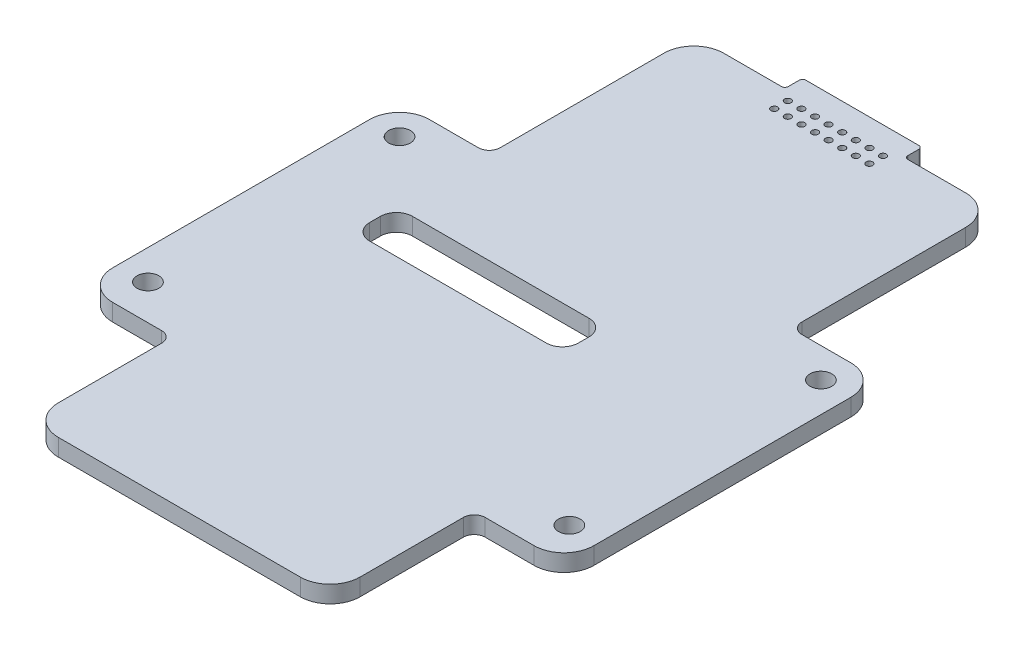
SolidWorks part; units mm, degrees
ref_plane "Front Plane" through (0, 0, 0) normal (0, 0, 1) x (1, 0, 0)
ref_plane "Top Plane" through (0, 0, 0) normal (0, 1, 0) x (1, 0, 0)
ref_plane "Right Plane" through (0, 0, 0) normal (1, 0, 0) x (0, 0, -1)
sketch "Sketch6" plane through (0, 3.4925, 0) normal (0, 1, 0) x (1, 0, 0)
  line L0 (19.685, 17.018) -> (15.113, 17.018) construction
  line L1 (11.303, 39.3065) -> (-11.303, 39.3065)
  line L2 (-14.097, 36.5125) -> (-14.097, 17.653)
  line L3 (11.303, 39.6875) -> (-11.303, 39.6875) construction
  line L4 (-14.478, 36.5125) -> (-14.478, 17.653) construction
  line L5 (-15.113, 17.018) -> (-19.685, 17.018) construction
  line L9 (14.478, 17.653) -> (14.478, 36.5125) construction
  line L10 (11.303, 39.6875) -> (-11.303, 39.6875)
  line L11 (-14.478, 36.5125) -> (-14.478, 17.653)
  line L12 (-15.113, 17.018) -> (-19.685, 17.018)
  line L16 (19.685, 17.018) -> (15.113, 17.018)
  line L17 (14.478, 17.653) -> (14.478, 36.5125)
  line L18 (-15.113, 16.637) -> (-19.685, 16.637)
  line L22 (19.685, 16.637) -> (15.113, 16.637)
  line L23 (14.097, 17.653) -> (14.097, 36.5125)
  line L24 (22.86, -13.843) -> (22.86, 13.843) construction
  line L25 (11.303, 35.7505) -> (5.9055, 35.7505)
  line L26 (-5.588, 36.068) -> (-5.588, 37.084)
  line L27 (-5.2705, 37.4015) -> (5.2705, 37.4015)
  line L28 (5.588, 37.084) -> (5.588, 36.068)
  line L29 (-5.9055, 35.7505) -> (-11.303, 35.7505)
  line L33 (15.113, -17.018) -> (19.685, -17.018) construction
  line L34 (14.478, -27.305) -> (14.478, -17.653) construction
  line L35 (-11.303, -30.48) -> (11.303, -30.48) construction
  line L36 (-14.478, -17.653) -> (-14.478, -27.305) construction
  line L37 (-19.685, -17.018) -> (-15.113, -17.018) construction
  line L38 (-22.86, 13.843) -> (-22.86, -13.843) construction
  line L39 (22.86, -13.843) -> (22.86, 13.843)
  line L40 (15.113, -17.018) -> (19.685, -17.018)
  line L41 (14.478, -27.305) -> (14.478, -17.653)
  line L42 (-11.303, -30.48) -> (11.303, -30.48)
  line L43 (-22.86, 13.843) -> (-22.86, -13.843) construction
  line L44 (-19.685, -17.018) -> (19.685, -17.018) construction
  line L45 (22.86, -13.843) -> (22.86, 13.843) construction
  line L46 (-22.479, 13.843) -> (-22.479, -13.843) construction
  line L47 (22.479, -13.843) -> (22.479, 13.843) construction
  line L48 (-14.478, -17.653) -> (-14.478, -27.305)
  line L49 (-19.685, -17.018) -> (-15.113, -17.018)
  line L50 (-22.86, 13.843) -> (-22.86, -13.843)
  line L51 (22.479, -13.843) -> (22.479, 13.843)
  line L52 (19.685, 16.637) -> (15.113, 16.637)
  line L53 (-19.685, -16.637) -> (19.685, -16.637) construction
  line L54 (14.097, 17.653) -> (14.097, 36.5125)
  line L55 (11.303, 39.3065) -> (-11.303, 39.3065)
  line L56 (-14.097, 36.5125) -> (-14.097, 17.653)
  line L57 (-15.113, 16.637) -> (-19.685, 16.637)
  line L58 (-22.479, 13.843) -> (-22.479, -13.843)
  line L59 (-19.685, -16.637) -> (-15.113, -16.637)
  line L60 (-14.097, -17.653) -> (-14.097, -27.305)
  line L61 (-11.303, -30.099) -> (11.303, -30.099)
  line L62 (14.097, -27.305) -> (14.097, -17.653)
  line L63 (15.113, -16.637) -> (19.685, -16.637)
  line L64 (15.113, -12.954) -> (19.685, -12.954)
  line L65 (14.097, -23.622) -> (14.097, -13.97)
  line L66 (-11.303, -26.416) -> (11.303, -26.416)
  line L67 (-14.097, -13.97) -> (-14.097, -23.622)
  line L68 (-19.685, -12.954) -> (-15.113, -12.954)
  arc A0 (22.86, 13.843) -> (19.685, 17.018) centre (19.685, 13.843) ccw construction
  arc A1 (14.478, 36.5125) -> (11.303, 39.6875) centre (11.303, 36.5125) ccw construction
  arc A2 (-11.303, 39.6875) -> (-14.478, 36.5125) centre (-11.303, 36.5125) ccw construction
  arc A3 (-15.113, 17.018) -> (-14.478, 17.653) centre (-15.113, 17.653) ccw construction
  arc A4 (-19.685, 17.018) -> (-22.86, 13.843) centre (-19.685, 13.843) ccw construction
  arc A7 (14.478, 17.653) -> (15.113, 17.018) centre (15.113, 17.653) ccw construction
  arc A8 (14.478, 36.5125) -> (11.303, 39.6875) centre (11.303, 36.5125) ccw
  arc A9 (-11.303, 39.6875) -> (-14.478, 36.5125) centre (-11.303, 36.5125) ccw
  arc A10 (-15.113, 17.018) -> (-14.478, 17.653) centre (-15.113, 17.653) ccw
  arc A11 (-19.685, 17.018) -> (-22.86, 13.843) centre (-19.685, 13.843) ccw
  arc A14 (22.86, 13.843) -> (19.685, 17.018) centre (19.685, 13.843) ccw
  arc A15 (14.478, 17.653) -> (15.113, 17.018) centre (15.113, 17.653) ccw
  arc A16 (-11.303, 39.3065) -> (-14.097, 36.5125) centre (-11.303, 36.5125) ccw
  arc A17 (-15.113, 16.637) -> (-14.097, 17.653) centre (-15.113, 17.653) ccw
  arc A18 (-19.685, 16.637) -> (-22.479, 13.843) centre (-19.685, 13.843) ccw
  arc A21 (22.479, 13.843) -> (19.685, 16.637) centre (19.685, 13.843) ccw
  arc A22 (14.097, 17.653) -> (15.113, 16.637) centre (15.113, 17.653) ccw
  arc A23 (14.097, 36.5125) -> (11.303, 39.3065) centre (11.303, 36.5125) ccw
  arc A24 (19.685, -17.018) -> (22.86, -13.843) centre (19.685, -13.843) ccw construction
  arc A25 (15.113, -17.018) -> (14.478, -17.653) centre (15.113, -17.653) ccw construction
  arc A26 (-11.303, 35.7505) -> (-14.097, 32.9565) centre (-11.303, 32.9565) ccw
  arc A27 (14.097, 32.9565) -> (11.303, 35.7505) centre (11.303, 32.9565) ccw
  arc A28 (5.588, 36.068) -> (5.9055, 35.7505) centre (5.9055, 36.068) ccw
  arc A29 (5.2705, 37.4015) -> (5.588, 37.084) centre (5.2705, 37.084) cw
  arc A30 (-5.588, 37.084) -> (-5.2705, 37.4015) centre (-5.2705, 37.084) cw
  arc A31 (-5.588, 36.068) -> (-5.9055, 35.7505) centre (-5.9055, 36.068) cw
  arc A36 (11.303, -30.48) -> (14.478, -27.305) centre (11.303, -27.305) ccw construction
  arc A37 (-14.478, -27.305) -> (-11.303, -30.48) centre (-11.303, -27.305) ccw construction
  arc A38 (-14.478, -17.653) -> (-15.113, -17.018) centre (-15.113, -17.653) ccw construction
  arc A39 (-22.86, -13.843) -> (-19.685, -17.018) centre (-19.685, -13.843) ccw construction
  arc A40 (19.685, -17.018) -> (22.86, -13.843) centre (19.685, -13.843) ccw
  arc A41 (15.113, -17.018) -> (14.478, -17.653) centre (15.113, -17.653) ccw
  arc A42 (11.303, -30.48) -> (14.478, -27.305) centre (11.303, -27.305) ccw
  arc A43 (-14.478, -27.305) -> (-11.303, -30.48) centre (-11.303, -27.305) ccw
  arc A44 (-14.478, -17.653) -> (-15.113, -17.018) centre (-15.113, -17.653) ccw
  arc A45 (-22.86, -13.843) -> (-19.685, -17.018) centre (-19.685, -13.843) ccw
  arc A46 (22.479, 13.843) -> (19.685, 16.637) centre (19.685, 13.843) ccw
  arc A47 (14.097, 17.653) -> (15.113, 16.637) centre (15.113, 17.653) ccw
  arc A49 (14.097, 36.5125) -> (11.303, 39.3065) centre (11.303, 36.5125) ccw
  arc A50 (-11.303, 39.3065) -> (-14.097, 36.5125) centre (-11.303, 36.5125) ccw
  arc A51 (-22.86, -13.843) -> (-19.685, -17.018) centre (-19.685, -13.843) ccw construction
  arc A52 (19.685, -17.018) -> (22.86, -13.843) centre (19.685, -13.843) ccw construction
  arc A53 (-22.479, -13.843) -> (-19.685, -16.637) centre (-19.685, -13.843) ccw construction
  arc A54 (19.685, -16.637) -> (22.479, -13.843) centre (19.685, -13.843) ccw construction
  arc A55 (-15.113, 16.637) -> (-14.097, 17.653) centre (-15.113, 17.653) ccw
  arc A56 (-19.685, 16.637) -> (-22.479, 13.843) centre (-19.685, 13.843) ccw
  arc A57 (-22.479, -13.843) -> (-19.685, -16.637) centre (-19.685, -13.843) ccw
  arc A58 (-14.097, -17.653) -> (-15.113, -16.637) centre (-15.113, -17.653) ccw
  arc A59 (-14.097, -27.305) -> (-11.303, -30.099) centre (-11.303, -27.305) ccw
  arc A60 (11.303, -30.099) -> (14.097, -27.305) centre (11.303, -27.305) ccw
  arc A61 (15.113, -16.637) -> (14.097, -17.653) centre (15.113, -17.653) ccw
  arc A62 (19.685, -16.637) -> (22.479, -13.843) centre (19.685, -13.843) ccw
  arc A63 (19.685, -12.954) -> (22.479, -10.16) centre (19.685, -10.16) ccw
  arc A64 (15.113, -12.954) -> (14.097, -13.97) centre (15.113, -13.97) ccw
  arc A65 (11.303, -26.416) -> (14.097, -23.622) centre (11.303, -23.622) ccw
  arc A66 (-14.097, -23.622) -> (-11.303, -26.416) centre (-11.303, -23.622) ccw
  arc A67 (-14.097, -13.97) -> (-15.113, -12.954) centre (-15.113, -13.97) ccw
  arc A68 (-22.479, -10.16) -> (-19.685, -12.954) centre (-19.685, -10.16) ccw
  point P66 (0, 37.4015)
  point P77 (-5.588, 35.7505)
  line M1 (14.478, 17.653) -> (14.478, -13.843)
  circle M9 centre (19.685, -6.223) radius 1.27
  circle M10 centre (19.685, 13.843) radius 1.27
  circle M73 centre (-7.0168, -21.209) radius 1.27
  arc M74 (14.478, -13.843) -> (11.303, -17.018) centre (11.303, -13.843) cw
  line M75 (11.303, -17.018) -> (-9.4615, -17.018)
  line M76 (-9.4615, -17.018) -> (-9.4615, -25.4)
  line M77 (-9.4615, -25.4) -> (12.7, -25.4)
  arc M78 (12.7, -25.4) -> (15.875, -22.225) centre (12.7, -22.225) ccw
  dimension "D8" = 0.3175
  dimension "D3" = 2
  dimension "D5" = 3.556
  dimension "D6" = 1.651
  dimension "D7" = 11.176
  dimension "D9" = 4.064
  dimension "D1" = 0.381
  dimension "D2" = 0.381
  dimension "D4" = 2
extrude "Boss-Extrude1" add sketch "Sketch6" along normal blind 1.6 contours L58 A68 L68 A67 L67 L60 A66 L66 A65 L65 A64 A22 L23 A27 L25 A28 L28 A29 L27 A30 L26 A31 L29 A26 L56 A17 L18 A18 M78 M77 M76 M75 M74 M1 | M9 | A64 L64 A63 L51 A21 L22 A22 M1 M9 M10 | M10 | A65 L62 L65 M78 M74 M75 M76 M77 M73 | M73
sketch "Sketch2" plane through (0, 3.4925, 0) normal (0, 1, 0) x (1, 0, 0)
  line L0 (0, -0.88) -> (0, 0.88) construction
  line L1 (19.685, 13.843) -> (19.685, -9.66) construction
  circle A0 centre (19.685, 13.843) radius 1.016
  circle A1 centre (19.685, -9.66) radius 1.016
  circle A2 centre (-19.685, -9.66) radius 1.016
  circle A3 centre (-19.685, 13.843) radius 1.016
  arc A4 (22.479, 13.843) -> (19.685, 16.637) centre (19.685, 13.843) ccw construction
  point P12 (19.685, -10.16)
  dimension "D1" = 2.032
  dimension "D2" = 0.5
extrude "Cut-Extrude1" cut sketch "Sketch2" along normal through all contours A3 | A0 | A1 | A2
sketch "Sketch3" plane through (0, 3.4925, 0) normal (0, 1, 0) x (1, 0, 0)
  line L0 (-4.6482, 33.8162) -> (-4.2418, 33.4098) construction
  circle A0 centre (-4.445, 33.613) radius 0.3048
  circle A1 centre (-3.175, 33.613) radius 0.3048
  circle A2 centre (-1.905, 33.613) radius 0.3048
  circle A3 centre (-0.635, 33.613) radius 0.3048
  circle A4 centre (0.635, 33.613) radius 0.3048
  circle A5 centre (1.905, 33.613) radius 0.3048
  circle A6 centre (3.175, 33.613) radius 0.3048
  circle A7 centre (4.445, 33.613) radius 0.3048
  circle A8 centre (-3.175, 34.883) radius 0.3048
  circle A9 centre (-1.905, 34.883) radius 0.3048
  circle A10 centre (-0.635, 34.883) radius 0.3048
  circle A11 centre (0.635, 34.883) radius 0.3048
  circle A12 centre (1.905, 34.883) radius 0.3048
  circle A13 centre (3.175, 34.883) radius 0.3048
  circle A14 centre (4.445, 34.883) radius 0.3048
  circle A15 centre (-4.445, 34.883) radius 0.3048
  dimension "D1" = 2
  dimension "D5" = 0.6096
  dimension "D2" = 1.27
  dimension "D3" = 1.27
  dimension "D4" = 8
extrude "Cut-Extrude2" cut sketch "Sketch3" along normal through all
sketch "Sketch7" plane through (0, 5.0925, 0) normal (0, 1, 0) x (1, 0, 0)
  line L6 (14.478, 17.5895) -> (14.478, 36.5125)
  line L7 (11.303, 39.6875) -> (-11.303, 39.6875)
  line L8 (-14.478, 36.5125) -> (-14.478, 5.5245)
  line L9 (-12.8905, 3.937) -> (4.1275, 3.937)
  line L10 (5.715, 5.5245) -> (5.715, 14.4145)
  line L11 (7.3025, 16.002) -> (12.8905, 16.002)
  line L12 (14.478, 17.5895) -> (14.478, 36.5125)
  line L13 (11.303, 39.6875) -> (-11.303, 39.6875)
  line L14 (-14.478, 36.5125) -> (-14.478, 5.5245)
  line L15 (-12.8905, 3.937) -> (4.1275, 3.937)
  line L16 (14.097, -23.622) -> (14.097, -13.97)
  line L17 (15.113, -12.954) -> (19.685, -12.954)
  line L18 (22.479, -10.16) -> (22.479, 13.843)
  line L19 (19.685, 16.637) -> (15.113, 16.637)
  line L20 (14.097, 17.653) -> (14.097, 32.9565)
  line L21 (11.303, 35.7505) -> (5.9055, 35.7505)
  line L22 (5.588, 36.068) -> (5.588, 37.084)
  line L23 (5.2705, 37.4015) -> (-5.2705, 37.4015)
  line L24 (-5.588, 37.084) -> (-5.588, 36.068)
  line L25 (-5.9055, 35.7505) -> (-11.303, 35.7505)
  line L26 (-14.097, 32.9565) -> (-14.097, 17.653)
  line L27 (-15.113, 16.637) -> (-19.685, 16.637)
  line L28 (-22.479, 13.843) -> (-22.479, -10.16)
  line L29 (-19.685, -12.954) -> (-15.113, -12.954)
  line L30 (-14.097, -13.97) -> (-14.097, -23.622)
  line L31 (-11.303, -26.416) -> (11.303, -26.416)
  line L32 (14.097, -23.622) -> (14.097, -13.97)
  line L33 (15.113, -12.954) -> (19.685, -12.954)
  line L34 (22.479, -10.16) -> (22.479, 13.843)
  line L35 (19.685, 16.637) -> (15.113, 16.637)
  line L36 (14.097, 17.653) -> (14.097, 32.9565)
  line L37 (11.303, 35.7505) -> (5.9055, 35.7505)
  line L38 (5.588, 36.068) -> (5.588, 37.084)
  line L39 (5.2705, 37.4015) -> (-5.2705, 37.4015)
  line L40 (-5.588, 37.084) -> (-5.588, 36.068)
  line L41 (-5.9055, 35.7505) -> (-11.303, 35.7505)
  line L42 (-14.097, 32.9565) -> (-14.097, 17.653)
  line L43 (-15.113, 16.637) -> (-19.685, 16.637)
  line L44 (-22.479, 13.843) -> (-22.479, -10.16)
  line L45 (-19.685, -12.954) -> (-15.113, -12.954)
  line L46 (-14.097, -13.97) -> (-14.097, -23.622)
  line L47 (-11.303, -26.416) -> (11.303, -26.416)
  line L48 (5.715, 5.5245) -> (5.715, 14.4145)
  line L49 (7.3025, 16.002) -> (12.8905, 16.002)
  arc A6 (12.8905, 16.002) -> (14.478, 17.5895) centre (12.8905, 17.5895) ccw
  arc A7 (14.478, 36.5125) -> (11.303, 39.6875) centre (11.303, 36.5125) ccw
  arc A8 (-11.303, 39.6875) -> (-14.478, 36.5125) centre (-11.303, 36.5125) ccw
  arc A9 (-14.478, 5.5245) -> (-12.8905, 3.937) centre (-12.8905, 5.5245) ccw
  arc A10 (4.1275, 3.937) -> (5.715, 5.5245) centre (4.1275, 5.5245) ccw
  arc A11 (7.3025, 16.002) -> (5.715, 14.4145) centre (7.3025, 14.4145) ccw
  arc A12 (12.8905, 16.002) -> (14.478, 17.5895) centre (12.8905, 17.5895) ccw
  arc A13 (14.478, 36.5125) -> (11.303, 39.6875) centre (11.303, 36.5125) ccw
  arc A14 (-11.303, 39.6875) -> (-14.478, 36.5125) centre (-11.303, 36.5125) ccw
  arc A15 (-14.478, 5.5245) -> (-12.8905, 3.937) centre (-12.8905, 5.5245) ccw
  arc A16 (11.303, -26.416) -> (14.097, -23.622) centre (11.303, -23.622) ccw
  arc A17 (15.113, -12.954) -> (14.097, -13.97) centre (15.113, -13.97) ccw
  arc A18 (19.685, -12.954) -> (22.479, -10.16) centre (19.685, -10.16) ccw
  arc A19 (22.479, 13.843) -> (19.685, 16.637) centre (19.685, 13.843) ccw
  arc A20 (14.097, 17.653) -> (15.113, 16.637) centre (15.113, 17.653) ccw
  arc A21 (14.097, 32.9565) -> (11.303, 35.7505) centre (11.303, 32.9565) ccw
  arc A22 (5.588, 36.068) -> (5.9055, 35.7505) centre (5.9055, 36.068) ccw
  arc A23 (5.588, 37.084) -> (5.2705, 37.4015) centre (5.2705, 37.084) ccw
  arc A24 (-5.2705, 37.4015) -> (-5.588, 37.084) centre (-5.2705, 37.084) ccw
  arc A25 (-5.9055, 35.7505) -> (-5.588, 36.068) centre (-5.9055, 36.068) ccw
  arc A26 (-11.303, 35.7505) -> (-14.097, 32.9565) centre (-11.303, 32.9565) ccw
  arc A27 (-15.113, 16.637) -> (-14.097, 17.653) centre (-15.113, 17.653) ccw
  arc A28 (-19.685, 16.637) -> (-22.479, 13.843) centre (-19.685, 13.843) ccw
  arc A29 (-22.479, -10.16) -> (-19.685, -12.954) centre (-19.685, -10.16) ccw
  arc A30 (-14.097, -13.97) -> (-15.113, -12.954) centre (-15.113, -13.97) ccw
  arc A31 (-14.097, -23.622) -> (-11.303, -26.416) centre (-11.303, -23.622) ccw
  arc A32 (11.303, -26.416) -> (14.097, -23.622) centre (11.303, -23.622) ccw
  arc A33 (15.113, -12.954) -> (14.097, -13.97) centre (15.113, -13.97) ccw
  arc A34 (19.685, -12.954) -> (22.479, -10.16) centre (19.685, -10.16) ccw
  arc A35 (22.479, 13.843) -> (19.685, 16.637) centre (19.685, 13.843) ccw
  arc A36 (14.097, 17.653) -> (15.113, 16.637) centre (15.113, 17.653) ccw
  arc A37 (14.097, 32.9565) -> (11.303, 35.7505) centre (11.303, 32.9565) ccw
  arc A38 (5.588, 36.068) -> (5.9055, 35.7505) centre (5.9055, 36.068) ccw
  arc A39 (5.588, 37.084) -> (5.2705, 37.4015) centre (5.2705, 37.084) ccw
  arc A40 (-5.2705, 37.4015) -> (-5.588, 37.084) centre (-5.2705, 37.084) ccw
  arc A41 (-5.9055, 35.7505) -> (-5.588, 36.068) centre (-5.9055, 36.068) ccw
  arc A42 (-11.303, 35.7505) -> (-14.097, 32.9565) centre (-11.303, 32.9565) ccw
  arc A43 (-15.113, 16.637) -> (-14.097, 17.653) centre (-15.113, 17.653) ccw
  arc A44 (-19.685, 16.637) -> (-22.479, 13.843) centre (-19.685, 13.843) ccw
  arc A45 (-22.479, -10.16) -> (-19.685, -12.954) centre (-19.685, -10.16) ccw
  arc A46 (-14.097, -13.97) -> (-15.113, -12.954) centre (-15.113, -13.97) ccw
  arc A47 (-14.097, -23.622) -> (-11.303, -26.416) centre (-11.303, -23.622) ccw
  arc A48 (4.1275, 3.937) -> (5.715, 5.5245) centre (4.1275, 5.5245) ccw
  arc A49 (7.3025, 16.002) -> (5.715, 14.4145) centre (7.3025, 14.4145) ccw
  point P47 (4.445, 34.883)
  dimension "D2" = 24.003
  dimension "D3" = 29.591
  dimension "D4" = 8.382
  dimension "D5" = 5.588
  dimension "D6" = 0
  dimension "D1" = 0
sketch "Sketch8" plane through (0, 3.4925, 0) normal (0, -1, 0) x (1, 0, 0)
  line L0 (-14.14, -6.01) -> (5.36, -6.01) construction
  line L1 (-12.64, -4.01) -> (3.86, -4.01)
  line L2 (-14.14, -5.51) -> (-14.14, -6.51)
  line L3 (-12.64, -8.01) -> (3.86, -8.01)
  line L4 (5.36, -5.51) -> (5.36, -6.51)
  arc A0 (3.86, -4.01) -> (5.36, -5.51) centre (3.86, -5.51) cw
  arc A1 (3.86, -8.01) -> (5.36, -6.51) centre (3.86, -6.51) ccw
  arc A2 (-14.14, -6.51) -> (-12.64, -8.01) centre (-12.64, -6.51) ccw
  arc A3 (-12.64, -4.01) -> (-14.14, -5.51) centre (-12.64, -5.51) ccw
  point P14 (-4.39, -6.01)
  dimension "D1" = 1.5
  dimension "D2" = 6.01
  dimension "D3" = 4.39
  dimension "D4" = 19.5
  dimension "D5" = 4
extrude "Cut-Extrude3" cut sketch "Sketch8" against normal through all
